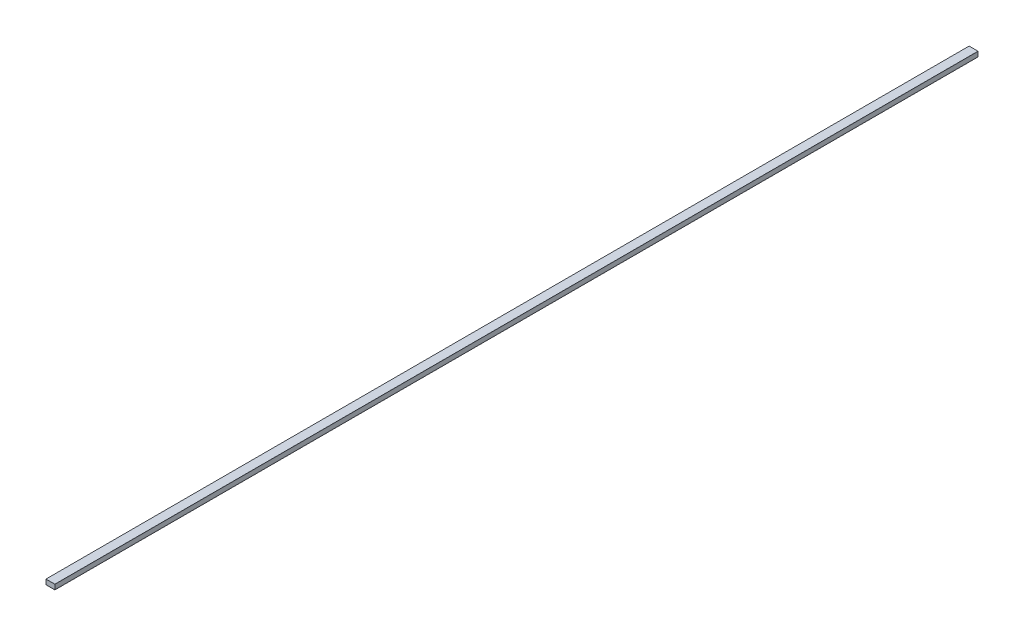
SolidWorks part; units mm, degrees
ref_plane "Front Plane" through (0, 0, 0) normal (0, 0, 1) x (1, 0, 0)
ref_plane "Top Plane" through (0, 0, 0) normal (0, 1, 0) x (1, 0, 0)
ref_plane "Right Plane" through (0, 0, 0) normal (1, 0, 0) x (0, 0, -1)
sketch "Core Sketch" plane through (0, 0, 0) normal (0, 0, 1) x (1, 0, 0)
  line L1 (-3.175, 1.5875) -> (3.175, 1.5875)
  line L2 (-3.175, 1.5875) -> (-3.175, -1.5875)
  line L3 (-3.175, -1.5875) -> (3.175, -1.5875)
  line L4 (3.175, 1.5875) -> (3.175, -1.5875)
  line L5 (-3.175, 1.5875) -> (3.175, -1.5875) construction
  line L6 (-3.175, -1.5875) -> (3.175, 1.5875) construction
  point P0 (0, 0)
  dimension "D1" = 3.175
  dimension "D2" = 6.35
sketch "Flange Sketch" plane through (0, 0, 0) normal (0, 0, 1) x (1, 0, 0)
  line L0 (0, 1.5875) -> (3.175, 1.5875)
  line L9 (-3.175, 1.5875) -> (3.175, 1.5875) construction
  line L10 (3.175, 1.5875) -> (3.175, 1.7875)
  line L11 (3.175, 1.7875) -> (-3.175, 1.7875)
  line L12 (-3.175, 1.7875) -> (-3.175, 1.5875)
  line L13 (-3.175, 1.5875) -> (0, 1.5875)
  line L14 (0, -1.5875) -> (3.175, -1.5875)
  line L15 (-3.175, -1.5875) -> (3.175, -1.5875) construction
  line L16 (3.175, -1.5875) -> (3.175, -1.7875)
  line L17 (3.175, -1.7875) -> (-3.175, -1.7875)
  line L18 (-3.175, -1.7875) -> (-3.175, -1.5875)
  line L19 (-3.175, -1.5875) -> (0, -1.5875)
  dimension "D1" = 6.35
extrude "Core" add sketch "Core Sketch" along normal mid plane 659.892
extrude "Flange" add sketch "Flange Sketch" along normal mid plane 659.892 separate body
equation "\"Fuse Width\"= 3.5in"
equation "\"Half Span\"= 11.24in"
equation "\"Total Span\"= \"Fuse Width\" + 2 * \"Half Span\""
equation "\"Core Width\"= 0.25in"
equation "\"Core Height\"= 0.125in"
equation "\"Flange Width\"= 0.25in"
equation "\"Flange Height\"= 0.2mm"
equation "\"D1@Core Sketch\" = \"Core Height\""
equation "\"D2@Core Sketch\" = \"Core Width\""
equation "\"D1@Flange Sketch\" = \"Flange Width\""
equation "\"D2@Flange Sketch\" = \"Flange Height\""
equation "\"D1@Core\" = \"Total Span\""
equation "\"D1@Flange\" = \"Total Span\""
